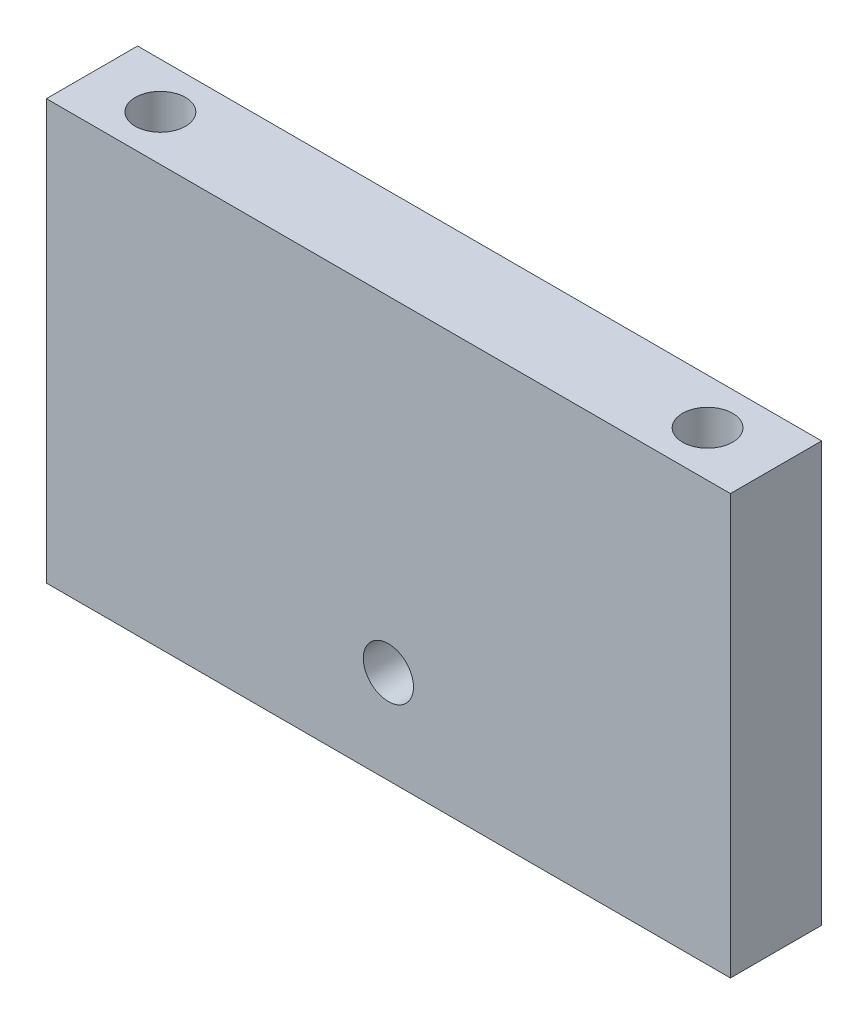
SolidWorks part; units mm, degrees
material "PET"
ref_plane "Front Plane" through (0, 0, 0) normal (0, 0, 1) x (1, 0, 0)
ref_plane "Top Plane" through (0, 0, 0) normal (0, 1, 0) x (1, 0, 0)
ref_plane "Right Plane" through (0, 0, 0) normal (1, 0, 0) x (0, 0, -1)
sketch "Sketch1" plane through (0, 0, 0) normal (0, 1, 0) x (1, 0, 0)
  line L0 (0, 5) -> (75, 5) construction
  line L1 (0, 0) -> (75, 0)
  line L2 (0, 0) -> (0, 10)
  line L3 (0, 10) -> (75, 10)
  line L4 (75, 0) -> (75, 10)
  line L5 (37.5, 10) -> (37.5, 0) construction
  circle A0 centre (7.5, 5) radius 2.75
  circle A1 centre (67.5, 5) radius 2.75
  dimension "D4" = 5.5
  dimension "D1" = 10
  dimension "D2" = 75
  dimension "D3" = 30
extrude "Boss-Extrude1" add sketch "Sketch1" along normal blind 46
sketch "Sketch3" plane through (0, 0, 0) normal (0, 0, 1) x (1, 0, 0)
  line L0 (37.5, 46) -> (37.5, 0) construction
  line L1 (0, 46) -> (75, 46) construction
  line L2 (0, 0) -> (75, 0) construction
  circle A0 centre (37.5, 10.25) radius 2.75
  dimension "D1" = 5.5
  dimension "D2" = 10.25
extrude "Cut-Extrude1" cut sketch "Sketch3" against normal blind 45
